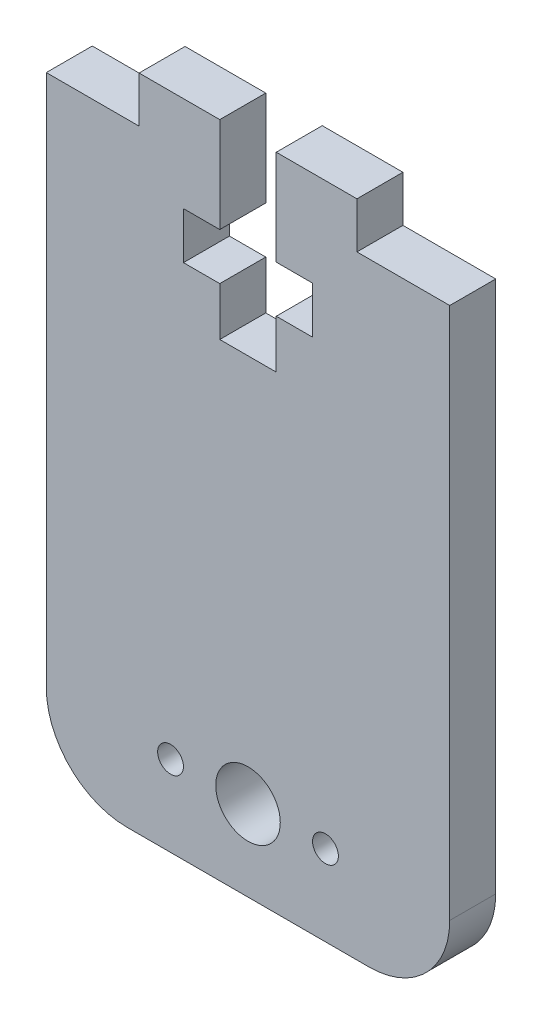
SolidWorks part; units mm, degrees
material "Pine"
ref_plane "Front" through (0, 0, 0) normal (0, 0, 1) x (1, 0, 0)
ref_plane "Top" through (0, 0, 0) normal (0, 1, 0) x (1, 0, 0)
ref_plane "Right" through (0, 0, 0) normal (1, 0, 0) x (0, 0, -1)
sketch "Sketch1" plane through (0, 0, 0) normal (0, 0, 1) x (1, 0, 0)
  line L1 (-12.5, 19) -> (12.5, 19)
  line L2 (-12.5, 19) -> (-12.5, -19)
  line L3 (-12.5, -19) -> (12.5, -19)
  line L4 (12.5, 19) -> (12.5, -19)
  line L5 (-12.5, 19) -> (12.5, -19) construction
  line L6 (-12.5, -19) -> (12.5, 19) construction
  point P0 (0, 0)
  dimension "D1" = 25
  dimension "D2" = 38
extrude "Boss-Extrude1" add sketch "Sketch1" along normal mid plane 2.85
sketch "Sketch2" plane through (0, 0, 1.425) normal (0, 0, 1) x (1, 0, 0)
  line L0 (-12.5, -19) -> (12.5, -19) construction
  line L1 (0, -14) -> (0, 0) construction
  circle A0 centre (0, -14) radius 2
  dimension "D1" = 4
  dimension "D2" = 5
extrude "Cut-Extrude1" cut sketch "Sketch2" against normal through all
sketch "Sketch3" plane through (0, 0, 1.425) normal (0, 0, 1) x (1, 0, 0)
  line L0 (-4.8, -14) -> (0, -14) construction
  line L1 (0, -14) -> (4.8, -14) construction
  circle A0 centre (-4.8, -14) radius 0.8
  circle A1 centre (4.8, -14) radius 0.8
  dimension "D1" = 1.6
  dimension "D2" = 9.6
extrude "Cut-Extrude2" cut sketch "Sketch3" against normal through all
sketch "Sketch4" plane through (0, 0, 1.425) normal (0, 0, 1) x (1, 0, 0)
  line L0 (12.5, 19) -> (-12.5, 19) construction
  line L1 (-6.75, 19) -> (-1.75, 19)
  line L2 (-6.75, 19) -> (-6.75, 21.85)
  line L3 (-6.75, 21.85) -> (-1.75, 21.85)
  line L4 (-1.75, 19) -> (-1.75, 21.85)
  line L5 (-6.75, 19) -> (-12.5, 19) construction
  line L6 (1.75, 19) -> (6.75, 19)
  line L7 (1.75, 19) -> (1.75, 21.85)
  line L8 (1.75, 21.85) -> (6.75, 21.85)
  line L9 (6.75, 19) -> (6.75, 21.85)
  line L10 (6.75, 19) -> (12.5, 19) construction
  dimension "D1" = 3.5
  dimension "D2" = 5
  dimension "D3" = 2.85
extrude "Boss-Extrude2" add sketch "Sketch4" against normal blind 2.85
sketch "Sketch5" plane through (0, 0, 1.425) normal (0, 0, 1) x (1, 0, 0)
  line L0 (-6.75, 19) -> (-12.5, 19) construction
  line L1 (-4, 15.95) -> (4, 15.95)
  line L2 (-4, 15.95) -> (-4, 13.05)
  line L3 (-4, 13.05) -> (4, 13.05)
  line L4 (4, 15.95) -> (4, 13.05)
  line L5 (-4, 15.95) -> (4, 13.05) construction
  line L6 (-4, 13.05) -> (4, 15.95) construction
  point P0 (0, 14.5)
  dimension "D1" = 8
  dimension "D2" = 2.9
  dimension "D3" = 4.5
extrude "Cut-Extrude3" cut sketch "Sketch5" against normal through all
sketch "Sketch6" plane through (0, 0, 1.425) normal (0, 0, 1) x (1, 0, 0)
  line L0 (-4, 13.05) -> (4, 13.05) construction
  line L1 (-1.75, 10.05) -> (1.75, 10.05)
  line L2 (-1.75, 10.05) -> (-1.75, 19)
  line L3 (-1.75, 19) -> (1.75, 19)
  line L4 (1.75, 10.05) -> (1.75, 19)
  line L5 (-1.75, 10.05) -> (1.75, 19) construction
  line L6 (-1.75, 19) -> (1.75, 10.05) construction
  point P0 (0, 14.525)
  dimension "D1" = 3
extrude "Cut-Extrude4" cut sketch "Sketch6" against normal through all
fillet "Fillet1" radius 5 2 edges at (12.5, -19, 0) (-12.5, -19, 0)
